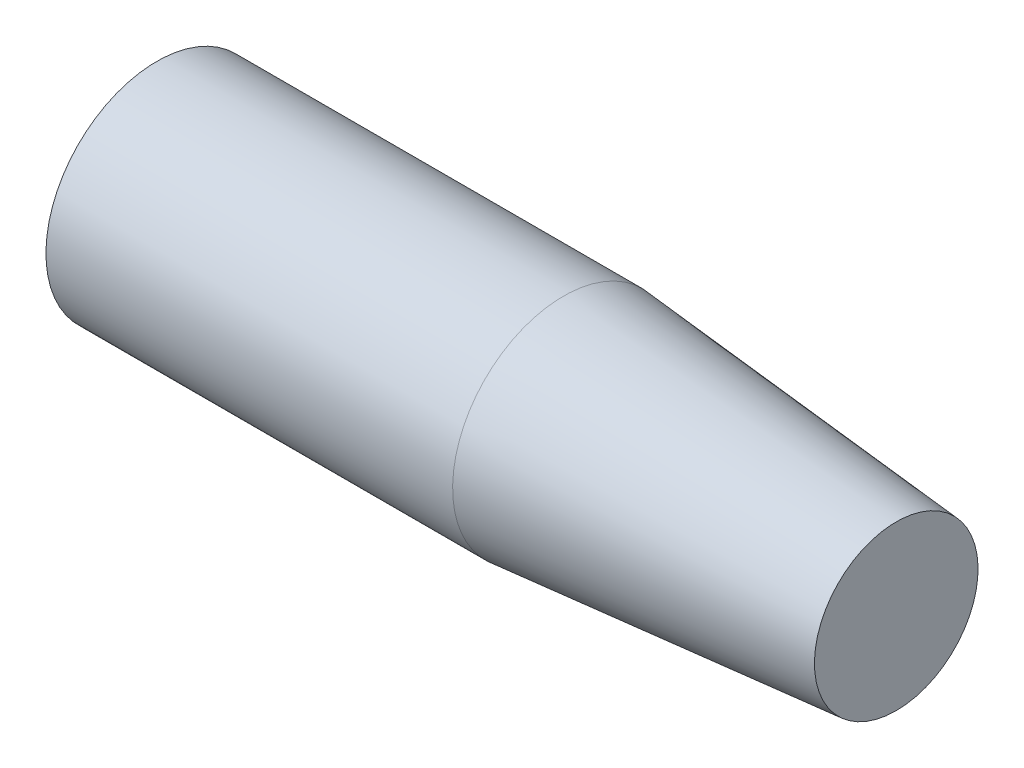
SolidWorks part; units mm, degrees
material "1.2083 (X40Cr14)"
ref_plane "Płaszczyzna przednia" through (0, 0, 0) normal (0, 0, 1) x (1, 0, 0)
ref_plane "Płaszczyzna górna" through (0, 0, 0) normal (0, 1, 0) x (1, 0, 0)
ref_plane "Płaszczyzna prawa" through (0, 0, 0) normal (1, 0, 0) x (0, 0, -1)
sketch "Szkic1" plane through (0, 0, 0) normal (0, 0, 1) x (1, 0, 0)
  line L0 (0, 0) -> (40, 0) construction
  line L1 (0, 0) -> (0, 3)
  line L2 (11, 3) -> (0, 3)
  line L3 (11, 3) -> (20, 2.2126)
  line L4 (20, 2.2126) -> (20, 0)
  line L5 (0, 0) -> (20, 0)
  dimension "D1" = 6
  dimension "D2" = 9
  dimension "D3" = 11
  dimension "D4" = 5
revolve "Obrót1" add sketch "Szkic1" angle 360 about L0
cosmetic thread "Oznaczenie gwintu1" parameters "D2"=4.891
sketch "Szkic2" plane through (0, 0, 0) normal (-1, 0, 0) x (0, 0, 1)
  line L1 (1.7321, 0) -> (0.866, 1.5)
  line L2 (0.866, 1.5) -> (-0.866, 1.5)
  line L3 (-0.866, 1.5) -> (-1.7321, 0)
  line L4 (-1.7321, 0) -> (-0.866, -1.5)
  line L5 (-0.866, -1.5) -> (0.866, -1.5)
  line L6 (0.866, -1.5) -> (1.7321, 0)
  circle A0 centre (0, 0) radius 1.5 construction
  dimension "D1" = 3
extrude "Wytnij-wyciągnięcie1" cut sketch "Szkic2" against normal blind 6
